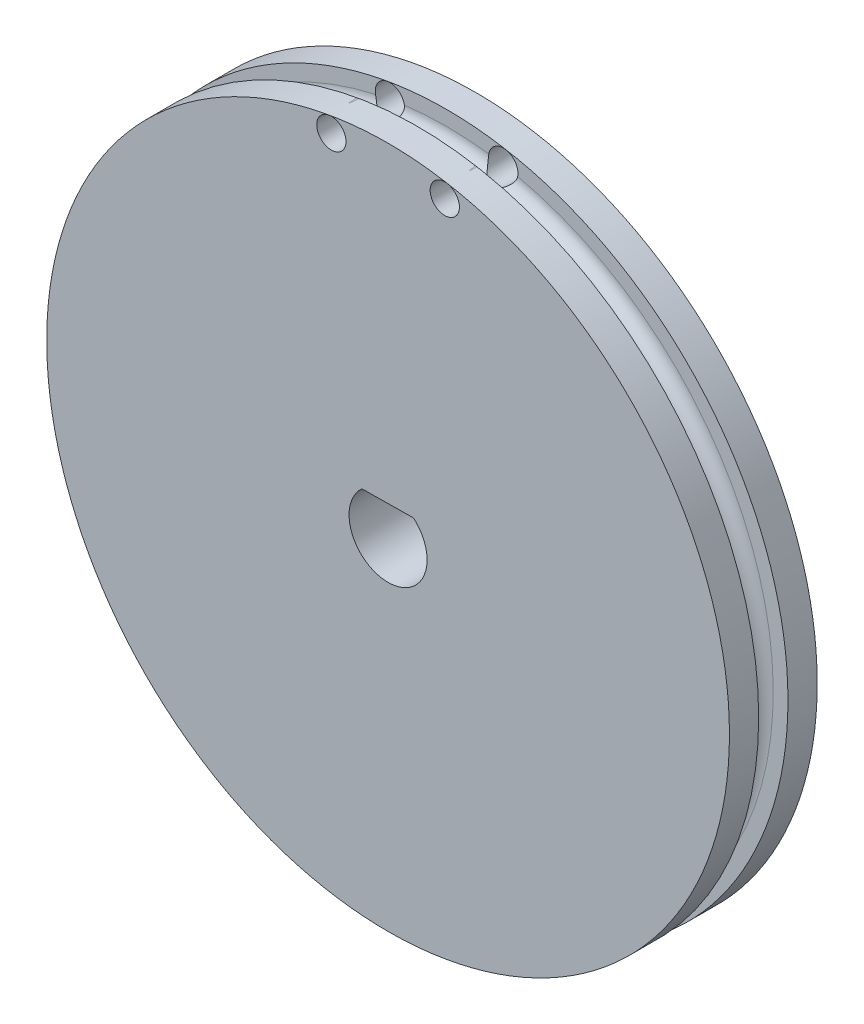
SolidWorks part; units mm, degrees
material "Stainless Steel (ferritic)"
ref_plane "Front Plane" through (0, 0, 0) normal (0, 0, 1) x (1, 0, 0)
ref_plane "Top Plane" through (0, 0, 0) normal (0, 1, 0) x (1, 0, 0)
ref_plane "Right Plane" through (0, 0, 0) normal (1, 0, 0) x (0, 0, -1)
sketch "Sketch2" plane through (0, 0, 0) normal (1, 0, 0) x (0, 0, -1)
  line L0 (-4.572, 0) -> (4.428, 0)
  line L1 (0, 20.2833) -> (0, -16.4952) construction
  line L2 (-4.572, 0) -> (-4.572, 35)
  line L3 (4.428, 0) -> (4.428, 35)
  line L4 (-4.572, 35) -> (-1.572, 35)
  line L5 (4.428, 35) -> (1.428, 35)
  line L6 (-1.572, 35) -> (-1.572, 33.49)
  line L7 (1.428, 33.49) -> (1.428, 35)
  arc A1 (-1.572, 33.49) -> (1.428, 33.49) centre (-0.072, 33.49) ccw
  dimension "D1" = 9
  dimension "D2" = 35
  dimension "D3" = 3
  dimension "D4" = 3
  dimension "D5" = 35
  dimension "D6" = 1.51
  dimension "D7" = 1.51
revolve "Revolve1" add sketch "Sketch2" angle 360 about L0
sketch "Sketch3" plane through (0, 0, -4.428) normal (0, 0, -1) x (-1, 0, 0)
  line L0 (0, 0) -> (0, 7.3583) construction
  line L1 (-10.3803, 3.1123) -> (10.7938, 2.8836) construction
  line L2 (-2.6132, 3.0284) -> (2.678, 2.9712)
  circle A0 centre (0, 0) radius 4 construction
  arc A1 (-2.6132, 3.0284) -> (2.678, 2.9712) centre (0, 0) ccw
  dimension "D2" = 8
  dimension "D1" = 3
extrude "Cut-Extrude1" cut sketch "Sketch3" against normal blind 9
sketch "Sketch4" plane through (0, 0, -4.428) normal (0, 0, -1) x (-1, 0, 0)
  line L0 (-54.9891, 0) -> (59.117, 0) construction
  line L1 (0, 51.6628) -> (0, 0) construction
  line L2 (0, 0) -> (-9.2544, 52.4842) construction
  line L3 (-9.2544, 52.4842) -> (0, 0) construction
  line L4 (0, 0) -> (9.282, 52.6409) construction
  circle A0 centre (-5.8155, 32.9812) radius 1.5
  circle A1 centre (5.8155, 32.9812) radius 1.5
  circle A3 centre (0, 0) radius 35 construction
  dimension "D3" = 33.49
  dimension "D1" = 10
  dimension "D2" = 10
  dimension "D4" = 33.49
extrude "Cut-Extrude10" cut sketch "Sketch4" against normal blind 33.49
